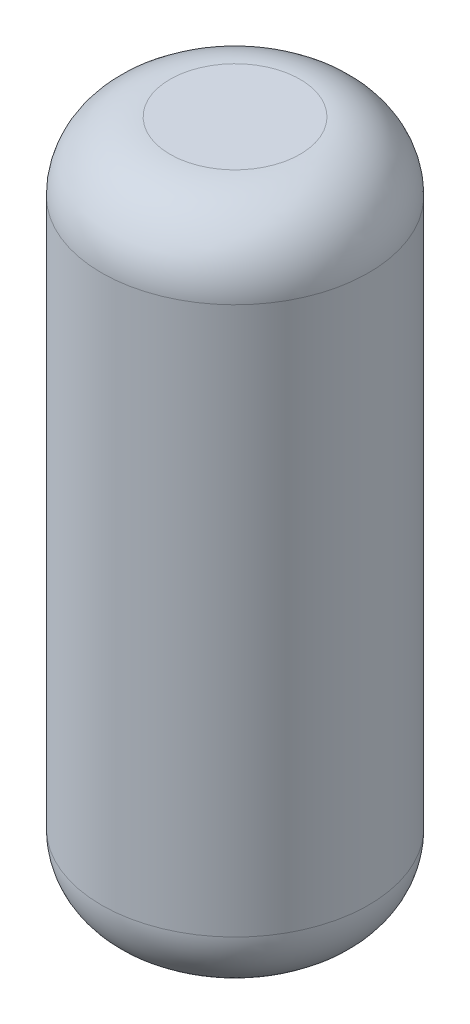
SolidWorks part; units mm, degrees
ref_plane "Plan de face" through (0, 0, 0) normal (0, 0, 1) x (1, 0, 0)
ref_plane "Plan de dessus" through (0, 0, 0) normal (0, 1, 0) x (1, 0, 0)
ref_plane "Plan de droite" through (0, 0, 0) normal (1, 0, 0) x (0, 0, -1)
sketch "Esquisse1" plane through (0, 0, 0) normal (0, 1, 0) x (1, 0, 0)
  circle A0 centre (0, 0) radius 1.95
  dimension "D1" = 3.9
extrude "Boss.-Extru.1" add sketch "Esquisse1" along normal blind 10
fillet "Congé1" radius 1 2 edges at (0, 10, 1.95) (0, 0, 1.95)
